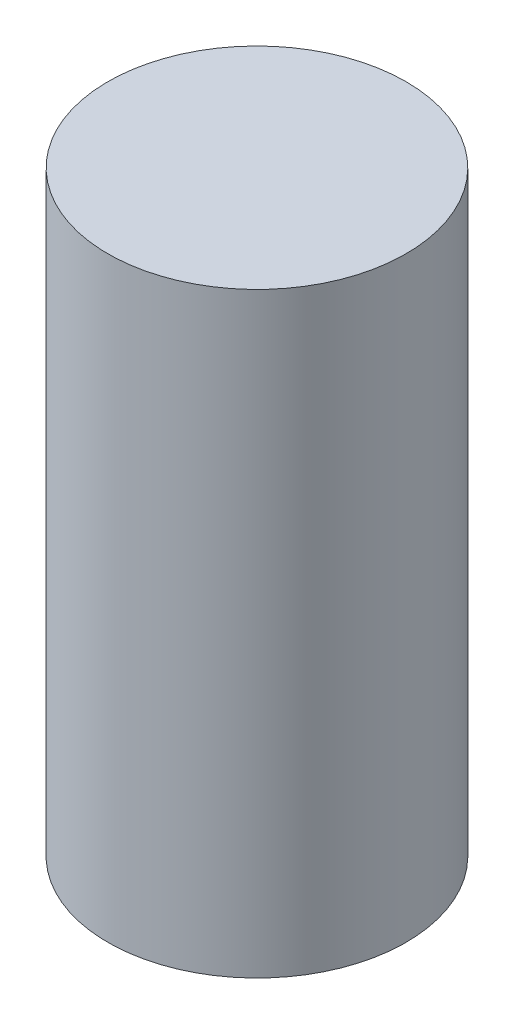
SolidWorks part; units mm, degrees
ref_plane "Front Plane" through (0, 0, 0) normal (0, 0, 1) x (1, 0, 0)
ref_plane "Top Plane" through (0, 0, 0) normal (0, 1, 0) x (1, 0, 0)
ref_plane "Right Plane" through (0, 0, 0) normal (1, 0, 0) x (0, 0, -1)
sketch "Sketch1" plane through (0, 0, 0) normal (0, 1, 0) x (1, 0, 0)
  circle A0 centre (0, 0) radius 19.05
  point P0 (0, 0)
  dimension "D1" = 38.1
extrude "Boss-Extrude1" add sketch "Sketch1" along normal blind 76.2
